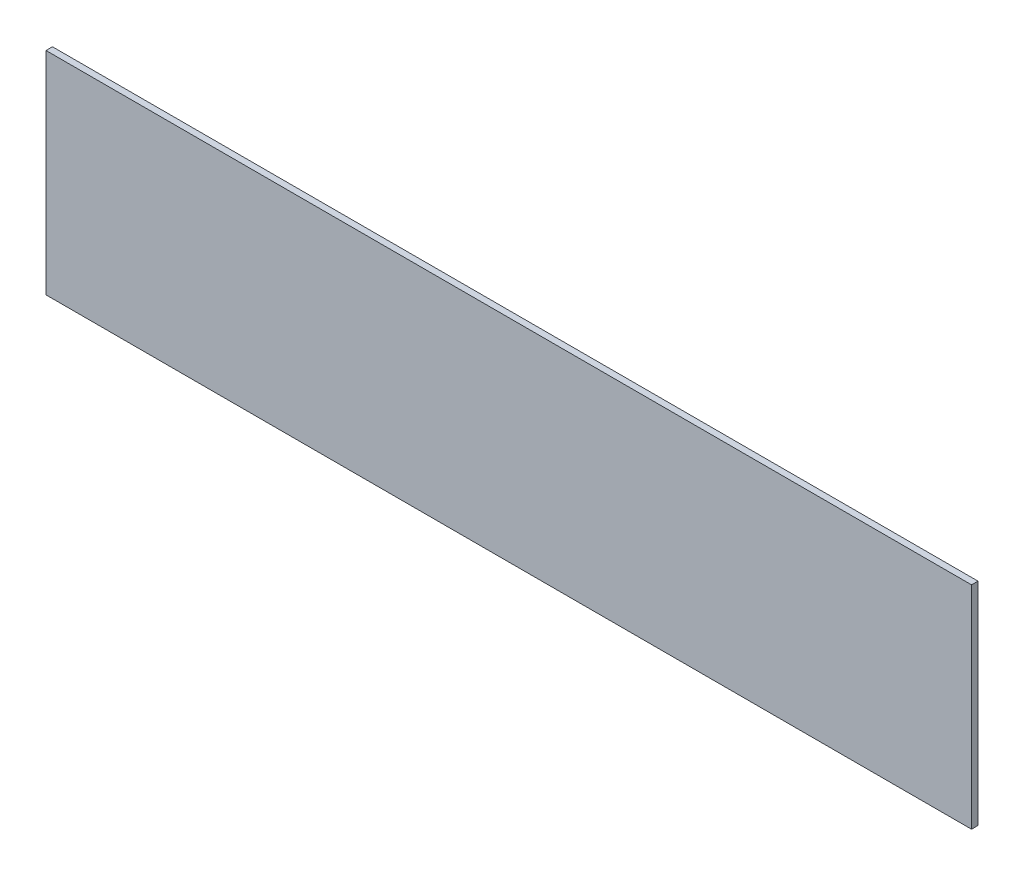
SolidWorks part; units mm, degrees
ref_plane "Plan de face" through (0, 0, 0) normal (0, 0, 1) x (1, 0, 0)
ref_plane "Plan de dessus" through (0, 0, 0) normal (0, 1, 0) x (1, 0, 0)
ref_plane "Plan de droite" through (0, 0, 0) normal (1, 0, 0) x (0, 0, -1)
sketch "Esquisse1" plane through (0, 0, 0) normal (0, 0, 1) x (1, 0, 0)
  line L1 (0, 0) -> (2580, 0)
  line L2 (0, 0) -> (0, 590)
  line L3 (0, 590) -> (2580, 590)
  line L4 (2580, 0) -> (2580, 590)
  dimension "D1" = 590
  dimension "D2" = 2580
extrude "Boss.-Extru.1" add sketch "Esquisse1" along normal blind 18
